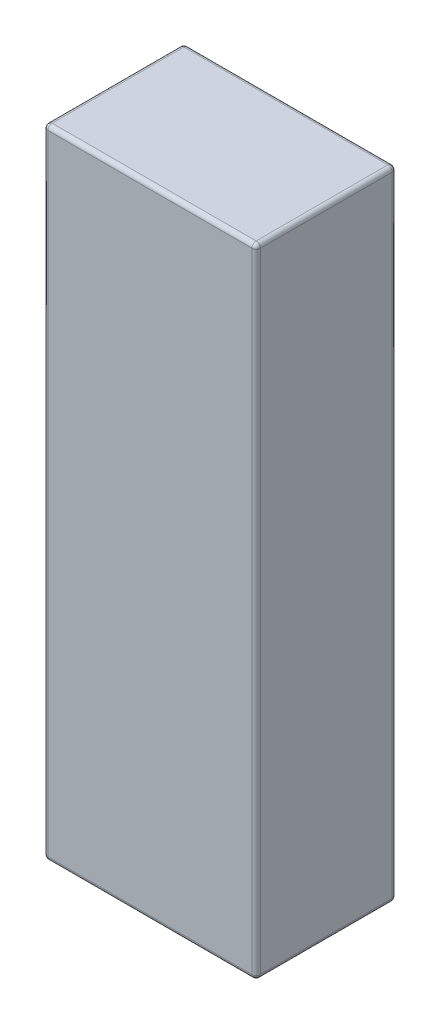
SolidWorks part; units mm, degrees
ref_plane "Front" through (0, 0, 0) normal (0, 0, 1) x (1, 0, 0)
ref_plane "Top" through (0, 0, 0) normal (0, 1, 0) x (1, 0, 0)
ref_plane "Right" through (0, 0, 0) normal (1, 0, 0) x (0, 0, -1)
sketch "Sketch1" plane through (0, 0, 0) normal (0, 1, 0) x (1, 0, 0)
  line L1 (-25, -16.5) -> (25, -16.5)
  line L2 (-25, -16.5) -> (-25, 16.5)
  line L3 (-25, 16.5) -> (25, 16.5)
  line L4 (25, -16.5) -> (25, 16.5)
  line L5 (-25, -16.5) -> (25, 16.5) construction
  line L6 (-25, 16.5) -> (25, -16.5) construction
  point P0 (0, 0)
  dimension "D1" = 50
  dimension "D2" = 33
extrude "Boss-Extrude1" add sketch "Sketch1" along normal mid plane 150
fillet "Fillet1" radius 1 12 edges at (25, 0, -16.5) (-25, 0, -16.5) (-25, 0, 16.5) (25, 0, 16.5) (0, -75, -16.5) (-25, -75, 0) (0, -75, 16.5) (25, -75, 0) (0, 75, 16.5) (-25, 75, 0) (0, 75, -16.5) (25, 75, 0)
